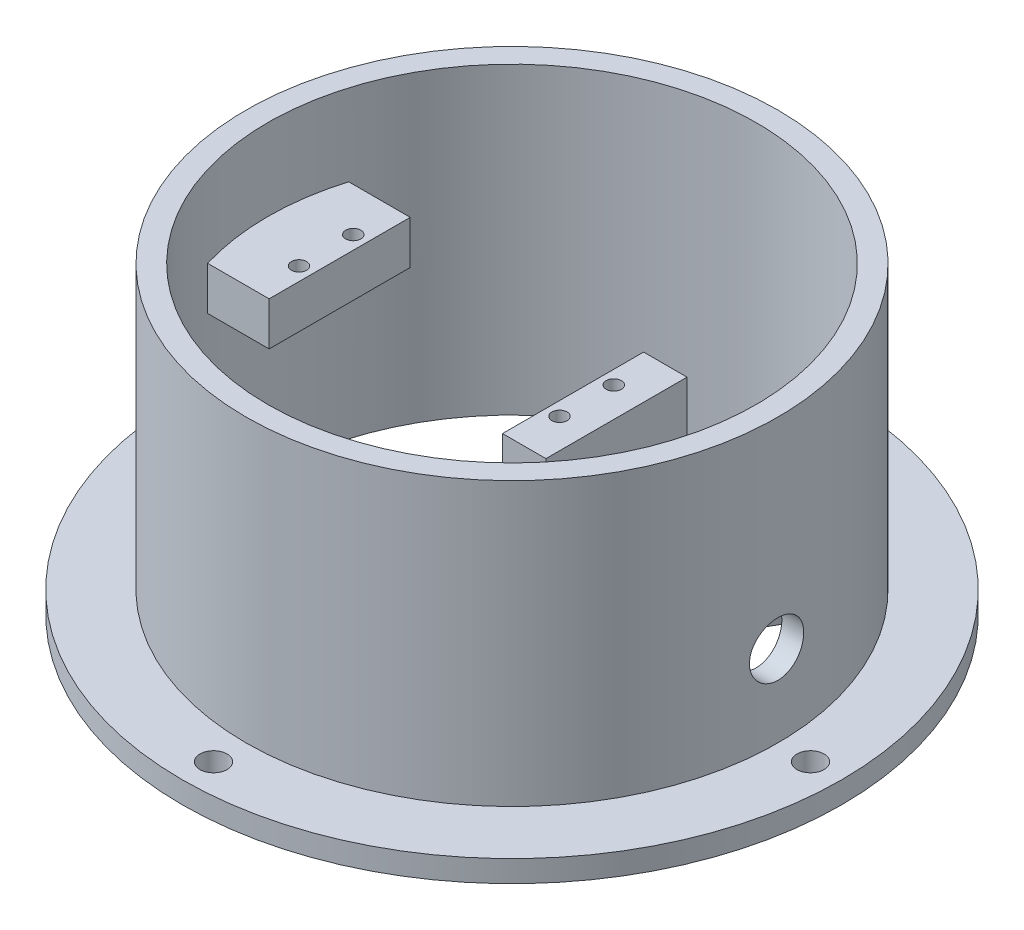
SolidWorks part; units mm, degrees
other "Markup1"
sketch "Sketch5" plane through (60.75, 56, 60.75) normal (0.0037, 0.9968, 0.0801) x (0.9898, -0.0151, 0.142)
ref_plane "Front Plane" through (0, 0, 0) normal (0, 0, 1) x (1, 0, 0)
ref_plane "Top Plane" through (0, 0, 0) normal (0, 1, 0) x (1, 0, 0)
ref_plane "Right Plane" through (0, 0, 0) normal (1, 0, 0) x (0, 0, -1)
sketch "Sketch1" plane through (0, 0, 0) normal (0, 1, 0) x (1, 0, 0)
  circle A0 centre (0, 0) radius 45
  circle A1 centre (0, 0) radius 60.75
  dimension "D1" = 90
  dimension "D2" = 121.5
extrude "Boss-Extrude1" add sketch "Sketch1" along normal blind 4
sketch "Sketch2" plane through (0, 4, 0) normal (0, 1, 0) x (1, 0, 0)
  circle A0 centre (0, 0) radius 45 construction
  circle A1 centre (0, 0) radius 45
  circle A2 centre (0, 0) radius 49
  dimension "D1" = 4
extrude "Boss-Extrude2" add sketch "Sketch2" along normal blind 52
sketch "Sketch4" plane through (0, 0, 0) normal (0, 0, 1) x (1, 0, 0)
  line L0 (0, 0) -> (0, 56) construction
  line L1 (49, 56) -> (-49, 56) construction
  line L2 (-60.75, 0) -> (60.75, 0) construction
  line L3 (11.25, 41) -> (19.25, 41)
  line L4 (11.25, 41) -> (11.25, 0)
  line L5 (11.25, 0) -> (19.25, 0)
  line L6 (19.25, 41) -> (19.25, 0)
  line L7 (-49, 56) -> (-49, 4) construction
  line L8 (-46.75, 41) -> (-31.75, 41)
  line L9 (-46.75, 41) -> (-46.75, 33)
  line L10 (-46.75, 33) -> (-31.75, 33)
  line L11 (-31.75, 41) -> (-31.75, 33)
  line L13 (45, 56) -> (-45, 56) construction
  dimension "D1" = 11.25
  dimension "D2" = 8
  dimension "D3" = 15
  dimension "D4" = 15
  dimension "D5" = 8
  dimension "D6" = 2.25
  dimension "D7" = 15
extrude "Boss-Extrude3" add sketch "Sketch4" along normal mid plane 26
sketch "Sketch6" plane through (11.25, 0, 0) normal (-1, 0, 0) x (0, 0, 1)
  line L0 (0, 0) -> (0, 56) construction
  line L1 (13, 0) -> (-13, 0) construction
  line L2 (45, 56) -> (-45, 56) construction
  line L3 (13, 41) -> (-13, 41) construction
  line L4 (-5, 5) -> (5, 5)
  line L5 (-5, 5) -> (-5, 31)
  line L6 (-5, 31) -> (5, 31)
  line L7 (5, 5) -> (5, 31)
  line L8 (-5, 5) -> (5, 31) construction
  line L9 (-5, 31) -> (5, 5) construction
  point P6 (0, 18)
  dimension "D1" = 5
  dimension "D2" = 10
  dimension "D3" = 10
extrude "Cut-Extrude1" cut sketch "Sketch6" against normal blind 26
sketch "Sketch7" plane through (11.25, 0, 0) normal (-1, 0, 0) x (0, 0, 1)
  line L0 (0, 41) -> (0, 0) construction
  line L1 (13, 41) -> (-13, 41) construction
  line L2 (-5, 5) -> (5, 5) construction
  circle A0 centre (0, 19) radius 5
  dimension "D1" = 10
  dimension "D2" = 14
extrude "Cut-Extrude2" cut sketch "Sketch7" against normal through all
sketch "Sketch8" plane through (0, 41, 0) normal (0, 1, 0) x (1, 0, 0)
  line L0 (-34.25, 13) -> (-34.25, -13) construction
  line L1 (-31.75, 13) -> (-43.0813, 13) construction
  line L2 (-31.75, -13) -> (-43.0813, -13) construction
  line L3 (-31.75, -13) -> (-31.75, 13) construction
  line L4 (-34.25, 0) -> (13.75, 0) construction
  line L5 (13.75, -13) -> (13.75, 13) construction
  line L6 (19.25, 13) -> (11.25, 13) construction
  circle A0 centre (-34.25, -5) radius 1.4
  circle A1 centre (13.75, -5) radius 1.4
  circle A2 centre (13.75, 5) radius 1.4
  circle A3 centre (-34.25, 5) radius 1.4
  point P16 (13.75, 0)
  dimension "D3" = 2.8
  dimension "D4" = 5
  dimension "D6" = 2.8
  dimension "D1" = 2.5
  dimension "D2" = 48
  dimension "D5" = 5
extrude "Cut-Extrude7" cut sketch "Sketch8" against normal blind 7.2
sketch "Sketch9" plane through (0, 0, 0) normal (0, -1, 0) x (1, 0, 0)
  line L0 (11.25, 0) -> (45, 0) construction
  line L1 (11.25, -13) -> (11.25, 13)
  line L2 (11.25, 13) -> (11.25, -13) construction
  line L3 (11.25, -13) -> (25.2498, -37.2484)
  line L4 (11.25, 13) -> (25.2498, 37.2484)
  line L5 (24.25, 19.5167) -> (27.3618, 24.9065)
  line L6 (24.25, -19.5167) -> (27.3618, -24.9065)
  line L7 (19.25, -10.8564) -> (19.25, 10.8564)
  line L8 (24.25, 19.5167) -> (24.25, -19.5167)
  line L9 (19.25, 10.8564) -> (27.3618, 24.9065) construction
  line L10 (19.25, -10.8564) -> (27.3618, -24.9065) construction
  circle A1 centre (0, 0) radius 45 construction
  arc A2 (25.2498, -37.2484) -> (25.2498, 37.2484) centre (0, 0) ccw
  arc A3 (27.3618, -24.9065) -> (27.3618, 24.9065) centre (0, 0) ccw
  line M8 (11.25, -13) -> (19.25, -13)
  line M9 (19.25, -13) -> (19.25, 13)
  line M10 (19.25, 13) -> (11.25, 13)
  dimension "D1" = 60
  dimension "D3" = 5
  dimension "D2" = 8
extrude "Boss-Extrude4" add sketch "Sketch9" against normal blind 4 contours L3 A2 L4 A3 L6 L8 L5 M10 M9 M8
sketch "Sketch12" plane through (0, 4, 0) normal (0, 1, 0) x (1, 0, 0)
  circle A0 centre (0, 0) radius 55 construction
  circle A1 centre (-55, 0) radius 2.5
  circle A2 centre (0, 55) radius 2.5
  circle A3 centre (55, 0) radius 2.5
  circle A4 centre (0, -55) radius 2.5
  point P14 (0, 0)
  dimension "D1" = 110
  dimension "D2" = 5
  dimension "D3" = 4
extrude "Cut-Extrude8" cut sketch "Sketch12" against normal through all
